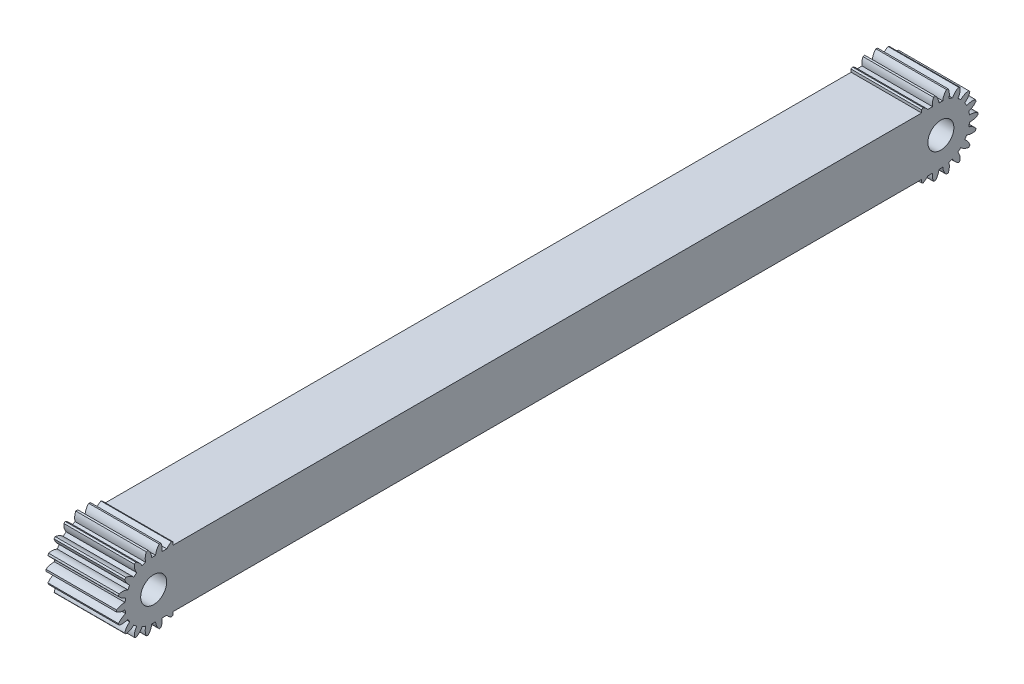
SolidWorks part; units mm, degrees
ref_plane "Front Plane" through (0, 0, 0) normal (0, 0, 1) x (1, 0, 0)
ref_plane "Top Plane" through (0, 0, 0) normal (0, 1, 0) x (1, 0, 0)
ref_plane "Right Plane" through (0, 0, 0) normal (1, 0, 0) x (0, 0, -1)
ref_plane "Plane1" through (7.2372, 0, 0) normal (1, 0, 0) x (0, 0, -1)
sketch "Sketch1" plane through (7.2372, 0, 0) normal (1, 0, 0) x (0, 0, -1)
  circle A0 centre (-1.3809, -5.469) radius 1.5
  arc A1 (-5.289, -2.3503) -> (-4.6009, -3.3151) centre (-3.5612, -1.8458) ccw
  arc A2 (-4.6009, -3.3151) -> (-4.8562, -3.7572) centre (-1.3809, -5.469) ccw
  arc A3 (-4.8562, -3.7572) -> (-6.0358, -3.6437) centre (-5.6088, -5.3924) ccw
  arc A4 (-6.0358, -3.6437) -> (-6.12, -3.875) centre (-1.3809, -5.469) ccw
  arc A5 (-6.12, -3.875) -> (-5.1434, -4.5463) centre (-4.6689, -2.81) ccw
  arc A6 (-5.1434, -4.5463) -> (-5.2321, -5.0491) centre (-1.3809, -5.469) ccw
  arc A7 (-5.2321, -5.0491) -> (-6.3794, -5.3459) centre (-5.38, -6.843) ccw
  arc A8 (-6.3794, -5.3459) -> (-6.3794, -5.592) centre (-1.3809, -5.469) ccw
  arc A9 (-6.3794, -5.592) -> (-5.2321, -5.8888) centre (-5.38, -4.0949) ccw
  arc A10 (-5.2321, -5.8888) -> (-5.1434, -6.3916) centre (-1.3809, -5.469) ccw
  arc A11 (-5.1434, -6.3916) -> (-6.12, -7.0629) centre (-4.6689, -8.1279) ccw
  arc A12 (-6.12, -7.0629) -> (-6.0358, -7.2942) centre (-1.3809, -5.469) ccw
  arc A13 (-6.0358, -7.2942) -> (-4.8562, -7.1807) centre (-5.6088, -5.5456) ccw
  arc A14 (-4.8562, -7.1807) -> (-4.6009, -7.6228) centre (-1.3809, -5.469) ccw
  arc A15 (-4.6009, -7.6228) -> (-5.289, -8.5877) centre (-3.5612, -9.0921) ccw
  arc A16 (-5.289, -8.5877) -> (-5.1309, -8.7762) centre (-1.3809, -5.469) ccw
  arc A17 (-5.1309, -8.7762) -> (-4.0612, -8.2661) centre (-5.3276, -6.987) ccw
  arc A18 (-4.0612, -8.2661) -> (-3.6701, -8.5942) centre (-1.3809, -5.469) ccw
  arc A19 (-3.6701, -8.5942) -> (-3.9867, -9.7362) centre (-2.1905, -9.6193) ccw
  arc A20 (-3.9867, -9.7362) -> (-3.7736, -9.8593) centre (-1.3809, -5.469) ccw
  arc A21 (-3.7736, -9.8593) -> (-2.9429, -9.0141) centre (-4.5704, -8.2453) ccw
  arc A22 (-2.9429, -9.0141) -> (-2.4631, -9.1887) centre (-1.3809, -5.469) ccw
  arc A23 (-2.4631, -9.1887) -> (-2.3701, -10.3701) centre (-0.7222, -9.6459) ccw
  arc A24 (-2.3701, -10.3701) -> (-2.1277, -10.4129) centre (-1.3809, -5.469) ccw
  arc A25 (-2.1277, -10.4129) -> (-1.6362, -9.3345) centre (-3.4285, -9.1687) ccw
  arc A26 (-1.6362, -9.3345) -> (-1.1256, -9.3345) centre (-1.3809, -5.469) ccw
  arc A27 (-1.1256, -9.3345) -> (-0.6341, -10.4129) centre (0.6667, -9.1687) ccw
  arc A28 (-0.6341, -10.4129) -> (-0.3917, -10.3701) centre (-1.3809, -5.469) ccw
  arc A29 (-0.3917, -10.3701) -> (-0.2987, -9.1887) centre (-2.0396, -9.6459) ccw
  arc A30 (-0.2987, -9.1887) -> (0.1811, -9.0141) centre (-1.3809, -5.469) ccw
  arc A31 (0.1811, -9.0141) -> (1.0118, -9.8593) centre (1.8086, -8.2453) ccw
  arc A32 (1.0118, -9.8593) -> (1.2249, -9.7362) centre (-1.3809, -5.469) ccw
  arc A33 (1.2249, -9.7362) -> (0.9083, -8.5942) centre (-0.5713, -9.6193) ccw
  arc A34 (0.9083, -8.5942) -> (1.2994, -8.2661) centre (-1.3809, -5.469) ccw
  arc A35 (1.2994, -8.2661) -> (2.3691, -8.7762) centre (2.5659, -6.987) ccw
  arc A36 (2.3691, -8.7762) -> (2.5273, -8.5877) centre (-1.3809, -5.469) ccw
  arc A37 (2.5273, -8.5877) -> (1.8392, -7.6228) centre (0.7994, -9.0921) ccw
  arc A38 (1.8392, -7.6228) -> (2.0944, -7.1807) centre (-1.3809, -5.469) ccw
  arc A39 (2.0944, -7.1807) -> (3.2741, -7.2942) centre (2.847, -5.5456) ccw
  arc A40 (3.2741, -7.2942) -> (3.3582, -7.0629) centre (-1.3809, -5.469) ccw
  arc A41 (3.3582, -7.0629) -> (2.3816, -6.3916) centre (1.9071, -8.1279) ccw
  arc A42 (2.3816, -6.3916) -> (2.4703, -5.8888) centre (-1.3809, -5.469) ccw
  arc A43 (2.4703, -5.8888) -> (3.6176, -5.592) centre (2.6183, -4.0949) ccw
  arc A44 (3.6176, -5.592) -> (3.6176, -5.3459) centre (-1.3809, -5.469) ccw
  arc A45 (3.6176, -5.3459) -> (2.4703, -5.0491) centre (2.6183, -6.843) ccw
  arc A46 (2.4703, -5.0491) -> (2.3816, -4.5463) centre (-1.3809, -5.469) ccw
  arc A47 (2.3816, -4.5463) -> (3.3582, -3.875) centre (1.9071, -2.81) ccw
  arc A48 (3.3582, -3.875) -> (3.2741, -3.6437) centre (-1.3809, -5.469) ccw
  arc A49 (3.2741, -3.6437) -> (2.0944, -3.7572) centre (2.847, -5.3924) ccw
  arc A50 (2.0944, -3.7572) -> (1.8392, -3.3151) centre (-1.3809, -5.469) ccw
  arc A51 (1.8392, -3.3151) -> (2.5273, -2.3503) centre (0.7994, -1.8458) ccw
  arc A52 (2.5273, -2.3503) -> (2.3691, -2.1617) centre (-1.3809, -5.469) ccw
  arc A53 (2.3691, -2.1617) -> (1.2994, -2.6718) centre (2.5659, -3.9509) ccw
  arc A54 (1.2994, -2.6718) -> (0.9083, -2.3437) centre (-1.3809, -5.469) ccw
  arc A55 (0.9083, -2.3437) -> (1.2249, -1.2017) centre (-0.5713, -1.3186) ccw
  arc A56 (1.2249, -1.2017) -> (1.0118, -1.0786) centre (-1.3809, -5.469) ccw
  arc A57 (1.0118, -1.0786) -> (0.1811, -1.9238) centre (1.8086, -2.6926) ccw
  arc A58 (0.1811, -1.9238) -> (-0.2987, -1.7492) centre (-1.3809, -5.469) ccw
  arc A59 (-0.2987, -1.7492) -> (-0.3917, -0.5678) centre (-2.0396, -1.292) ccw
  arc A60 (-0.3917, -0.5678) -> (-0.6341, -0.525) centre (-1.3809, -5.469) ccw
  arc A61 (-0.6341, -0.525) -> (-1.1256, -1.6034) centre (0.6667, -1.7692) ccw
  arc A62 (-1.1256, -1.6034) -> (-1.6362, -1.6034) centre (-1.3809, -5.469) ccw
  arc A63 (-1.6362, -1.6034) -> (-2.1277, -0.525) centre (-3.4285, -1.7692) ccw
  arc A64 (-2.1277, -0.525) -> (-2.3701, -0.5678) centre (-1.3809, -5.469) ccw
  arc A65 (-2.3701, -0.5678) -> (-2.4631, -1.7492) centre (-0.7222, -1.292) ccw
  arc A66 (-2.4631, -1.7492) -> (-2.9429, -1.9238) centre (-1.3809, -5.469) ccw
  arc A67 (-2.9429, -1.9238) -> (-3.7736, -1.0786) centre (-4.5704, -2.6926) ccw
  arc A68 (-3.7736, -1.0786) -> (-3.9867, -1.2017) centre (-1.3809, -5.469) ccw
  arc A69 (-3.9867, -1.2017) -> (-3.6701, -2.3437) centre (-2.1905, -1.3186) ccw
  arc A70 (-3.6701, -2.3437) -> (-4.0612, -2.6718) centre (-1.3809, -5.469) ccw
  arc A71 (-4.0612, -2.6718) -> (-5.1309, -2.1617) centre (-5.3276, -3.9509) ccw
  arc A72 (-5.1309, -2.1617) -> (-5.289, -2.3503) centre (-1.3809, -5.469) ccw
extrude "Boss-Extrude1" add sketch "Sketch1" against normal blind 9.5
sketch "Sketch6" plane through (7.2372, 0, 0) normal (1, 0, 0) x (0, 0, -1)
  circle A0 centre (-1.3809, -5.469) radius 1.75
extrude "Cut-Extrude1" cut sketch "Sketch6" against normal blind 10
sketch "Sketch7" plane through (-2.2628, 0, 0) normal (-1, 0, 0) x (0, 0, 1)
  line L0 (-104.6191, -1.595) -> (1.3809, -1.595)
  line L1 (-104.6191, -9.343) -> (1.3809, -9.343)
  arc A0 (-104.6191, -1.595) -> (-104.6191, -9.343) centre (-104.6191, -5.469) ccw
  arc A1 (1.3809, -9.343) -> (1.3809, -1.595) centre (1.3809, -5.469) ccw
  circle A2 centre (-104.6191, -5.469) radius 1.75
  circle A3 centre (1.3809, -5.469) radius 1.75
extrude "Boss-Extrude2" add sketch "Sketch7" against normal blind 9.5
ref_plane "Plane2" through (-2.2628, 0, 0) normal (-1, 0, 0) x (0, 0, 1)
sketch "Sketch12" plane through (-2.2628, 0, 0) normal (-1, 0, 0) x (0, 0, 1)
  arc A0 (-101.3991, -3.3151) -> (-100.711, -2.3503) centre (-102.4388, -1.8458) ccw
  arc A1 (-100.711, -2.3503) -> (-100.8691, -2.1617) centre (-104.6191, -5.469) ccw
  arc A2 (-100.8691, -2.1617) -> (-101.9388, -2.6718) centre (-100.6724, -3.9509) ccw
  arc A3 (-101.9388, -2.6718) -> (-102.3299, -2.3437) centre (-104.6191, -5.469) ccw
  arc A4 (-102.3299, -2.3437) -> (-102.0133, -1.2017) centre (-103.8095, -1.3186) ccw
  arc A5 (-102.0133, -1.2017) -> (-102.2264, -1.0786) centre (-104.6191, -5.469) ccw
  arc A6 (-102.2264, -1.0786) -> (-103.0571, -1.9238) centre (-101.4296, -2.6926) ccw
  arc A7 (-103.0571, -1.9238) -> (-103.5369, -1.7492) centre (-104.6191, -5.469) ccw
  arc A8 (-103.5369, -1.7492) -> (-103.6299, -0.5678) centre (-105.2778, -1.292) ccw
  arc A9 (-103.6299, -0.5678) -> (-103.8723, -0.525) centre (-104.6191, -5.469) ccw
  arc A10 (-103.8723, -0.525) -> (-104.3638, -1.6034) centre (-102.5715, -1.7692) ccw
  arc A11 (-104.3638, -1.6034) -> (-104.8744, -1.6034) centre (-104.6191, -5.469) ccw
  arc A12 (-104.8744, -1.6034) -> (-105.3659, -0.525) centre (-106.6667, -1.7692) ccw
  arc A13 (-105.3659, -0.525) -> (-105.6083, -0.5678) centre (-104.6191, -5.469) ccw
  arc A14 (-105.6083, -0.5678) -> (-105.7013, -1.7492) centre (-103.9604, -1.292) ccw
  arc A15 (-105.7013, -1.7492) -> (-106.1811, -1.9238) centre (-104.6191, -5.469) ccw
  arc A16 (-106.1811, -1.9238) -> (-107.0118, -1.0786) centre (-107.8086, -2.6926) ccw
  arc A17 (-107.0118, -1.0786) -> (-107.2249, -1.2017) centre (-104.6191, -5.469) ccw
  arc A18 (-107.2249, -1.2017) -> (-106.9083, -2.3437) centre (-105.4287, -1.3186) ccw
  arc A19 (-106.9083, -2.3437) -> (-107.2994, -2.6718) centre (-104.6191, -5.469) ccw
  arc A20 (-107.2994, -2.6718) -> (-108.3691, -2.1617) centre (-108.5659, -3.9509) ccw
  arc A21 (-108.3691, -2.1617) -> (-108.5273, -2.3503) centre (-104.6191, -5.469) ccw
  arc A22 (-108.5273, -2.3503) -> (-107.8392, -3.3151) centre (-106.7994, -1.8458) ccw
  arc A23 (-107.8392, -3.3151) -> (-108.0944, -3.7572) centre (-104.6191, -5.469) ccw
  arc A24 (-108.0944, -3.7572) -> (-109.2741, -3.6437) centre (-108.847, -5.3924) ccw
  arc A25 (-109.2741, -3.6437) -> (-109.3582, -3.875) centre (-104.6191, -5.469) ccw
  arc A26 (-109.3582, -3.875) -> (-108.3816, -4.5463) centre (-107.9071, -2.81) ccw
  arc A27 (-108.3816, -4.5463) -> (-108.4703, -5.0491) centre (-104.6191, -5.469) ccw
  arc A28 (-108.4703, -5.0491) -> (-109.6176, -5.3459) centre (-108.6183, -6.843) ccw
  arc A29 (-109.6176, -5.3459) -> (-109.6176, -5.592) centre (-104.6191, -5.469) ccw
  arc A30 (-109.6176, -5.592) -> (-108.4703, -5.8888) centre (-108.6183, -4.0949) ccw
  arc A31 (-108.4703, -5.8888) -> (-108.3816, -6.3916) centre (-104.6191, -5.469) ccw
  arc A32 (-108.3816, -6.3916) -> (-109.3582, -7.0629) centre (-107.9071, -8.1279) ccw
  arc A33 (-109.3582, -7.0629) -> (-109.2741, -7.2942) centre (-104.6191, -5.469) ccw
  arc A34 (-109.2741, -7.2942) -> (-108.0944, -7.1807) centre (-108.847, -5.5456) ccw
  arc A35 (-108.0944, -7.1807) -> (-107.8392, -7.6228) centre (-104.6191, -5.469) ccw
  arc A36 (-107.8392, -7.6228) -> (-108.5273, -8.5877) centre (-106.7994, -9.0921) ccw
  arc A37 (-108.5273, -8.5877) -> (-108.3691, -8.7762) centre (-104.6191, -5.469) ccw
  arc A38 (-108.3691, -8.7762) -> (-107.2994, -8.2661) centre (-108.5659, -6.987) ccw
  arc A39 (-107.2994, -8.2661) -> (-106.9083, -8.5942) centre (-104.6191, -5.469) ccw
  arc A40 (-106.9083, -8.5942) -> (-107.2249, -9.7362) centre (-105.4287, -9.6193) ccw
  arc A41 (-107.2249, -9.7362) -> (-107.0118, -9.8593) centre (-104.6191, -5.469) ccw
  arc A42 (-107.0118, -9.8593) -> (-106.1811, -9.0141) centre (-107.8086, -8.2453) ccw
  arc A43 (-106.1811, -9.0141) -> (-105.7013, -9.1887) centre (-104.6191, -5.469) ccw
  arc A44 (-105.7013, -9.1887) -> (-105.6083, -10.3701) centre (-103.9604, -9.6459) ccw
  arc A45 (-105.6083, -10.3701) -> (-105.3659, -10.4129) centre (-104.6191, -5.469) ccw
  arc A46 (-105.3659, -10.4129) -> (-104.8744, -9.3345) centre (-106.6667, -9.1687) ccw
  arc A47 (-104.8744, -9.3345) -> (-104.3638, -9.3345) centre (-104.6191, -5.469) ccw
  arc A48 (-104.3638, -9.3345) -> (-103.8723, -10.4129) centre (-102.5715, -9.1687) ccw
  arc A49 (-103.8723, -10.4129) -> (-103.6299, -10.3701) centre (-104.6191, -5.469) ccw
  arc A50 (-103.6299, -10.3701) -> (-103.5369, -9.1887) centre (-105.2778, -9.6459) ccw
  arc A51 (-103.5369, -9.1887) -> (-103.0571, -9.0141) centre (-104.6191, -5.469) ccw
  arc A52 (-103.0571, -9.0141) -> (-102.2264, -9.8593) centre (-101.4296, -8.2453) ccw
  arc A53 (-102.2264, -9.8593) -> (-102.0133, -9.7362) centre (-104.6191, -5.469) ccw
  arc A54 (-102.0133, -9.7362) -> (-102.3299, -8.5942) centre (-103.8095, -9.6193) ccw
  arc A55 (-102.3299, -8.5942) -> (-101.9388, -8.2661) centre (-104.6191, -5.469) ccw
  arc A56 (-101.9388, -8.2661) -> (-100.8691, -8.7762) centre (-100.6724, -6.987) ccw
  arc A57 (-100.8691, -8.7762) -> (-100.711, -8.5877) centre (-104.6191, -5.469) ccw
  arc A58 (-100.711, -8.5877) -> (-101.3991, -7.6228) centre (-102.4388, -9.0921) ccw
  arc A59 (-101.3991, -7.6228) -> (-101.1438, -7.1807) centre (-104.6191, -5.469) ccw
  arc A60 (-101.1438, -7.1807) -> (-99.9642, -7.2942) centre (-100.3912, -5.5456) ccw
  arc A61 (-99.9642, -7.2942) -> (-99.88, -7.0629) centre (-104.6191, -5.469) ccw
  arc A62 (-99.88, -7.0629) -> (-100.8566, -6.3916) centre (-101.3311, -8.1279) ccw
  arc A63 (-100.8566, -6.3916) -> (-100.7679, -5.8888) centre (-104.6191, -5.469) ccw
  arc A64 (-100.7679, -5.8888) -> (-99.6206, -5.592) centre (-100.62, -4.0949) ccw
  arc A65 (-99.6206, -5.592) -> (-99.6206, -5.3459) centre (-104.6191, -5.469) ccw
  arc A66 (-99.6206, -5.3459) -> (-100.7679, -5.0491) centre (-100.62, -6.843) ccw
  arc A67 (-100.7679, -5.0491) -> (-100.8566, -4.5463) centre (-104.6191, -5.469) ccw
  arc A68 (-100.8566, -4.5463) -> (-99.88, -3.875) centre (-101.3311, -2.81) ccw
  arc A69 (-99.88, -3.875) -> (-99.9642, -3.6437) centre (-104.6191, -5.469) ccw
  arc A70 (-99.9642, -3.6437) -> (-101.1438, -3.7572) centre (-100.3912, -5.3924) ccw
  arc A71 (-101.1438, -3.7572) -> (-101.3991, -3.3151) centre (-104.6191, -5.469) ccw
  circle A72 centre (-104.6191, -5.469) radius 1.75
extrude "Boss-Extrude3" add sketch "Sketch12" against normal blind 9.5
